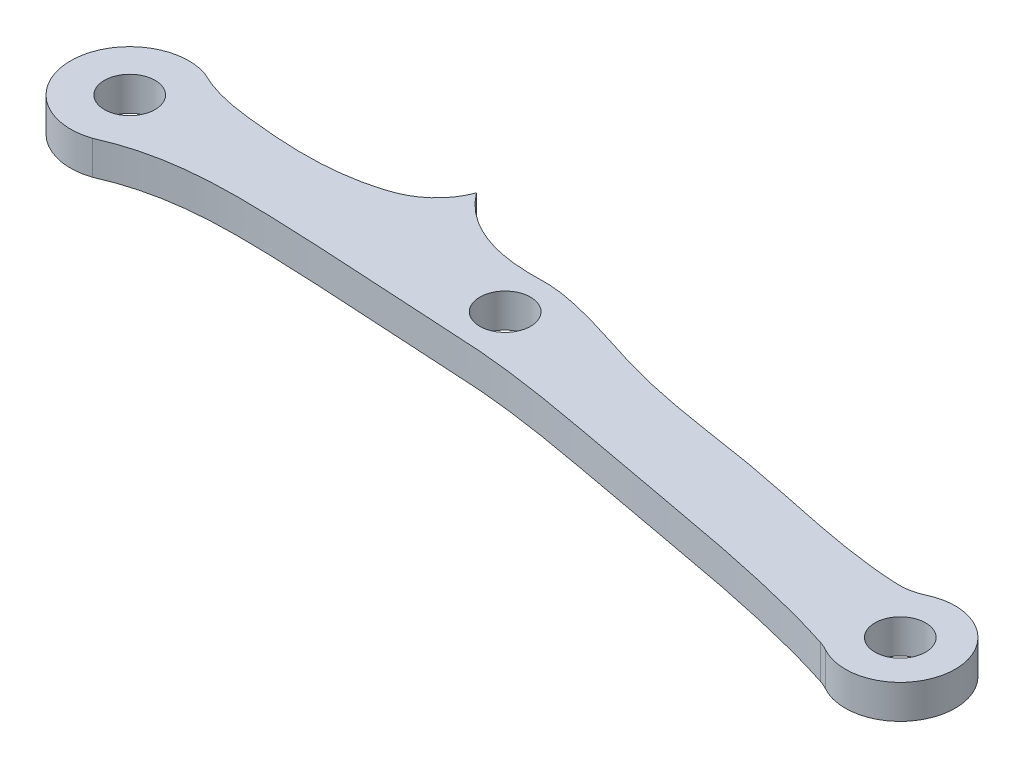
SolidWorks part; units mm, degrees
ref_plane "Front Plane" through (0, 0, 0) normal (0, 0, 1) x (1, 0, 0)
ref_plane "Top Plane" through (0, 0, 0) normal (0, 1, 0) x (1, 0, 0)
ref_plane "Right Plane" through (0, 0, 0) normal (1, 0, 0) x (0, 0, -1)
sketch "Sketch1" plane through (0, 0, 0) normal (0, 1, 0) x (1, 0, 0)
  line L0 (0, 0) -> (222, 0)
  line L1 (222, 0) -> (505.6246, -50.0107)
  circle A0 centre (0, 0) radius 15
  circle A1 centre (222, 0) radius 15
  circle A2 centre (505.6246, -50.0107) radius 15
  arc A3 (11.2278, 33.1502) -> (11.2278, -33.1502) centre (0, 0) ccw
  arc A4 (489.8325, -78.4159) -> (491.6711, -20.6585) centre (505.6246, -50.0107) ccw
  arc A5 (484.5907, -76.1257) -> (489.8325, -78.4159) centre (475.2552, -104.6362) cw
  arc A6 (477.4495, -23.5342) -> (491.6711, -20.6585) centre (478.791, 6.4358) ccw
  spline S0 degree 3 poles (11.2278, 33.1502) (24.9359, 26.1256) (59.9256, 21.3057) (100.8009, 19.3912) (138.4495, 31.2641) (149.1807, 42.659) (152.57, 52.4464) knots 0 0 0 0 0.279361 0.721039 0.798624 1 1 1 1
  spline S1 degree 3 poles (152.57, 52.4464) (169.2163, 30.2513) (199.4998, 25.9855) (229.531, 27.5997) (258.1156, 19.3713) (295.6782, 6.7854) (325.979, 0.9766) (396.0411, -9.0671) (440.0323, -21.8594) (477.4495, -23.5342) knots 0 0 0 0 0.15665 0.187429 0.294416 0.335474 0.556953 0.622372 0.961981 0.961981 0.961981 0.961981
  spline S2 degree 3 poles (11.2278, -33.1502) (41.4168, -19.5458) (109.617, -19.5944) (185.8237, -25.1066) (260.8893, -28.7263) (314.9989, -40.1035) (397.0298, -54.5301) (449.7715, -64.7244) (484.5907, -76.1257) knots 0 0 0 0 0.199281 0.408197 0.458288 0.673317 0.728276 0.981 0.981 0.981 0.981
  point P18 (0, 0)
  point P21 (0, 0)
  point P23 (152.57, 52.4464)
  point P25 (119.1257, 27.1593)
  point P27 (128.3685, 28.3134)
  point P28 (44.1587, 23.7774)
  point P29 (217.7125, 26.9096)
  point P30 (268.6904, 15.8046)
  dimension "D4" = 70
  dimension "D5" = 30
  dimension "D6" = 65
  dimension "D7" = 30
  dimension "D8" = 30
  dimension "D9" = 30
  dimension "D1" = 222
  dimension "D2" = 288
  dimension "D3" = 190
extrude "Boss-Extrude1" add sketch "Sketch1" along normal blind 20
